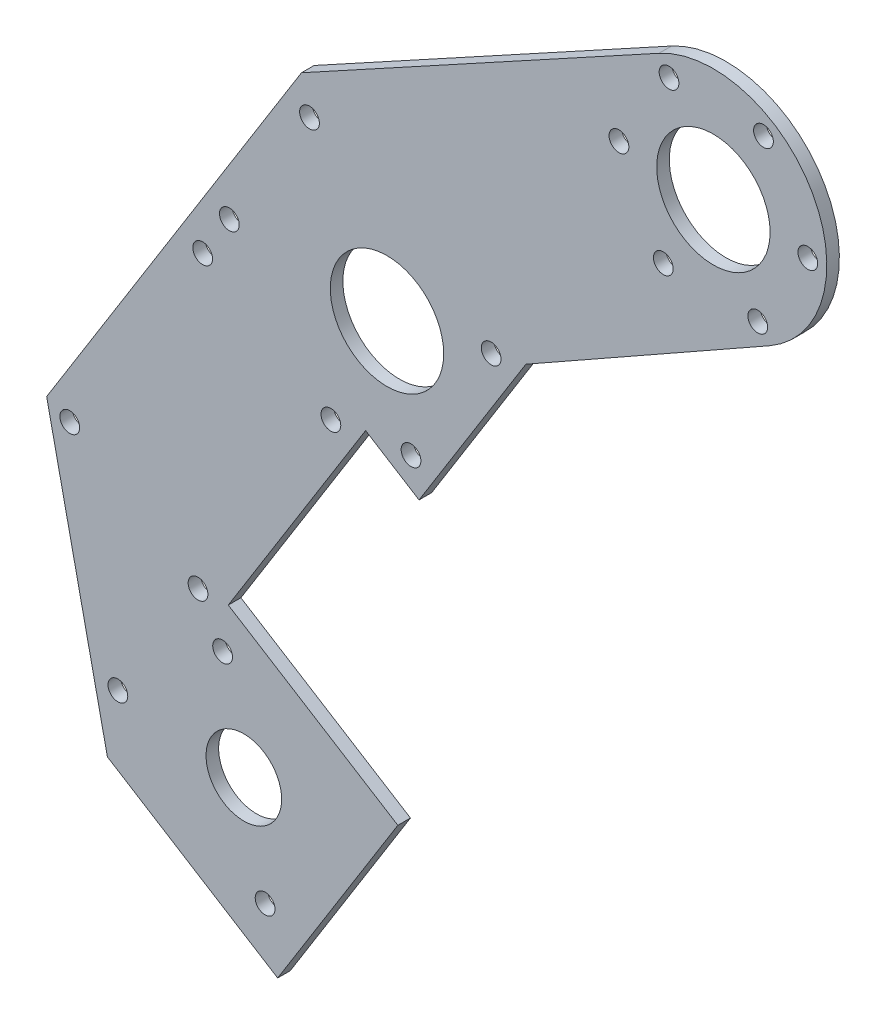
SolidWorks part; units mm, degrees
ref_plane "Front Plane" through (0, 0, 0) normal (0, 0, 1) x (1, 0, 0)
ref_plane "Top Plane" through (0, 0, 0) normal (0, 1, 0) x (1, 0, 0)
ref_plane "Right Plane" through (0, 0, 0) normal (1, 0, 0) x (0, 0, -1)
sketch "Sketch1" plane through (0, 0, -14.1946) normal (0, 0, 1) x (1, 0, 0)
  line L0 (-11.4036, 461.0409) -> (18.8813, 509.5069)
  line L1 (-54.3079, 487.8505) -> (-69.6155, 558.824)
  line L2 (18.8813, 509.5069) -> (-23.8465, 536.2061)
  line L3 (10.7592, 591.5868) -> (-157.4902, 322.3315) construction
  line L4 (-11.4036, 461.0409) -> (-54.3079, 487.8505)
  line L5 (-69.6155, 558.824) -> (-5.4017, 661.5875)
  line L6 (-23.8465, 536.2061) -> (10.7592, 591.5868)
  line L8 (-115.7964, 730.5698) -> (51.1419, 626.2552) construction
  line L9 (-142.7163, 687.4889) -> (24.222, 583.1743) construction
  line L10 (51.1419, 626.2552) -> (112.462, 660.9373)
  line L11 (10.7592, 591.5868) -> (24.222, 583.1743)
  line L13 (24.222, 583.1743) -> (51.1419, 626.2552)
  line L16 (-5.4017, 661.5875) -> (84.678, 710.8773)
  circle A2 centre (16.1415, 618.1747) radius 14.2875
  circle A3 centre (-19.9236, 500.5437) radius 9.525
  circle A5 centre (98.3945, 685.8096) radius 14.2875
  arc A7 (112.462, 660.9373) -> (84.678, 710.8773) centre (98.3945, 685.8096) ccw
  point P33 (98.3945, 685.8096)
extrude "Boss-Extrude1" add sketch "Sketch1" along normal blind 3.175
sketch "Sketch17" plane through (0, 0, -11.0196) normal (0, 0, 1) x (1, 0, 0)
  line L0 (-14.5684, 475.7147) -> (-19.9236, 500.5437)
  line L1 (-19.9236, 500.5437) -> (-25.2787, 525.3728)
  line L2 (16.1415, 618.1747) -> (37.6819, 604.7147) construction
  line L12 (24.222, 583.1743) -> (51.1419, 626.2552) construction
  line L13 (37.6819, 604.7147) -> (27.587, 588.5594) construction
  line L14 (27.587, 588.5594) -> (22.2019, 591.9244) construction
  line L15 (22.2019, 591.9244) -> (-28.9566, 623.8918) construction
  line L16 (-5.4017, 661.5875) -> (-69.6155, 558.824) construction
  line L17 (-28.9566, 623.8918) -> (-23.5715, 620.5268) construction
  line L18 (-23.5715, 620.5268) -> (-3.3816, 652.8374) construction
  line L19 (-3.3816, 652.8374) -> (42.3918, 624.2351) construction
  line L20 (10.7592, 591.5868) -> (5.3741, 594.9518) construction
  line L21 (5.3741, 594.9518) -> (-31.4748, 535.9811) construction
  line L22 (-31.4748, 535.9811) -> (-51.6648, 503.6705) construction
  line L23 (5.3741, 594.9518) -> (2.0091, 589.5667) construction
  line L24 (-31.4748, 535.9811) -> (-63.7855, 556.1711) construction
  line L25 (2.0091, 589.5667) -> (-30.3015, 609.7566) construction
  circle A0 centre (-19.9236, 500.5437) radius 25.4
hole_wizard "#10 Clearance Hole2" positions "Sketch20" profile "Sketch21" hole size "#10" standard "ANSI Inch" end condition through all
sketch "Sketch20" plane through (0, 0, -11.0196) normal (0, 0, 1) x (1, 0, 0)
  point P0 (-25.2787, 525.3728)
  point P3 (-14.5684, 475.7147)
  point P24 (-3.3816, 652.8374)
  point P27 (42.3918, 624.2351)
  point P30 (22.2019, 591.9244)
  point P33 (-23.5715, 620.5268)
  point P42 (-31.4748, 535.9811)
  point P45 (-63.7855, 556.1711)
  point P48 (-51.6648, 503.6705)
  point P54 (2.0091, 589.5667)
  point P57 (-30.3015, 609.7566)
sketch "Sketch21" plane through (-25.2787, 525.3728, -11.0196) normal (1, 0, 0) x (0, -1, 0)
  line L0 (0, 0) -> (0, 3.175)
  line L1 (0, 3.175) -> (2.4892, 3.175)
  line L2 (2.4892, 3.175) -> (2.4892, 0)
  line L5 (2.4892, 0) -> (0, 0)
  line L11 (0, -6.35) -> (0, 107.95) construction
  dimension "Thru Hole Dia." = 4.9784
  dimension "Thru Hole Depth" = 3.175
sketch "Sketch22" plane through (0, 0, -11.0196) normal (0, 0, 1) x (1, 0, 0)
  line L0 (98.3945, 685.8096) -> (111.0132, 706.0038) construction
  line L2 (111.0132, 706.0038) -> (87.2152, 706.8348) construction
  line L3 (87.2152, 706.8348) -> (74.5965, 686.6407) construction
  line L4 (74.5965, 686.6407) -> (85.7758, 665.6155) construction
  line L5 (85.7758, 665.6155) -> (109.5738, 664.7845) construction
  line L6 (109.5738, 664.7845) -> (122.1925, 684.9786) construction
  line L7 (122.1925, 684.9786) -> (111.0132, 706.0038) construction
  circle A0 centre (98.3945, 685.8096) radius 23.8125 construction
  point P3 (81.6813, 702.3014)
  point P10 (98.3945, 685.8096)
hole_wizard "#10 Clearance Hole3" positions "Sketch23" profile "Sketch24" hole size "#10" standard "ANSI Inch" end condition through all
sketch "Sketch23" plane through (0, 0, -11.0196) normal (0, 0, 1) x (1, 0, 0)
  point P0 (111.0132, 706.0038)
  point P3 (122.1925, 684.9786)
  point P6 (109.5738, 664.7845)
  point P9 (85.7758, 665.6155)
  point P12 (74.5965, 686.6407)
  point P15 (87.2152, 706.8348)
sketch "Sketch24" plane through (111.0132, 706.0038, -11.0196) normal (1, 0, 0) x (0, -1, 0)
  line L0 (0, 0) -> (0, 3.175)
  line L1 (0, 3.175) -> (2.4892, 3.175)
  line L2 (2.4892, 3.175) -> (2.4892, 0)
  line L5 (2.4892, 0) -> (0, 0)
  line L11 (0, -6.35) -> (0, 107.95) construction
  dimension "Thru Hole Dia." = 4.9784
  dimension "Thru Hole Depth" = 3.175
